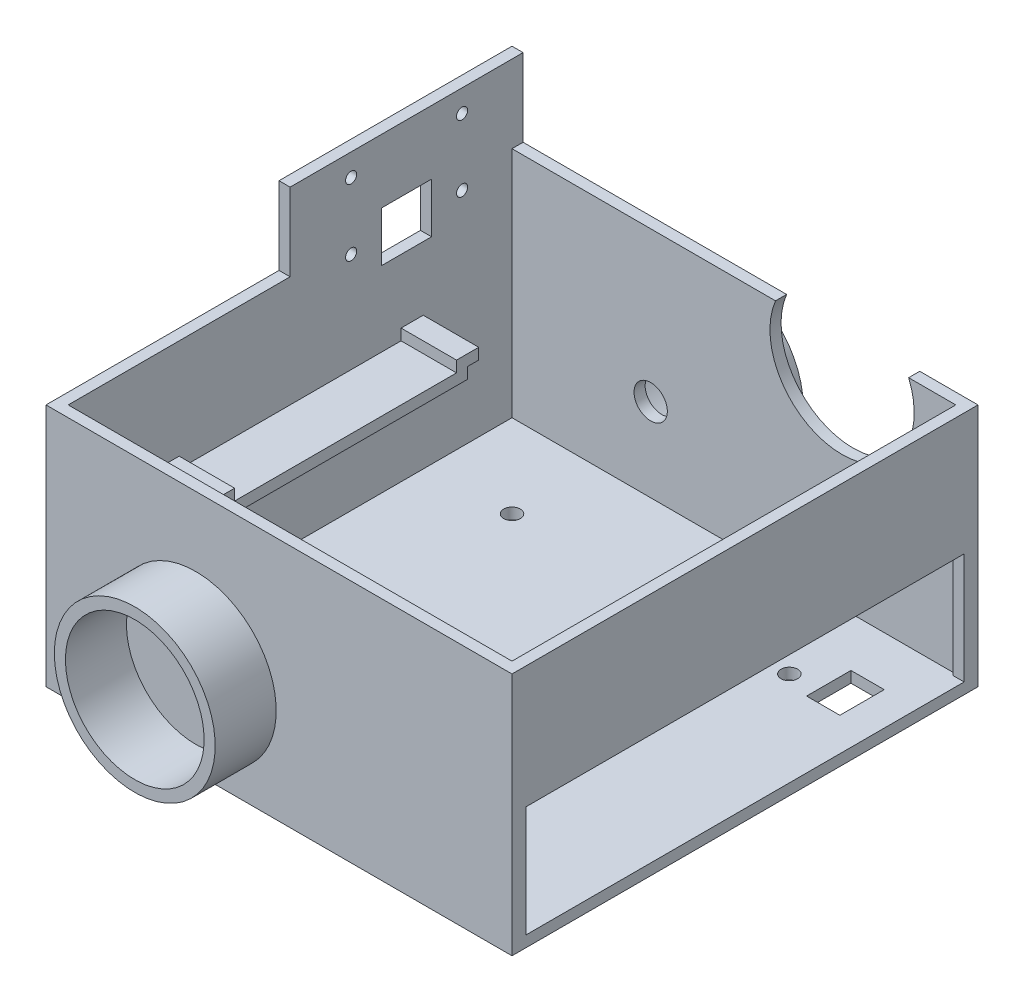
SolidWorks part; units mm, degrees
ref_plane "Front Plane" through (0, 0, 0) normal (0, 0, 1) x (1, 0, 0)
ref_plane "Top Plane" through (0, 0, 0) normal (0, 1, 0) x (1, 0, 0)
ref_plane "Right Plane" through (0, 0, 0) normal (1, 0, 0) x (0, 0, -1)
sketch "Sketch1" plane through (0, 0, 0) normal (0, 1, 0) x (1, 0, 0)
  line L1 (-39, -39) -> (39, -39) construction
  line L2 (-39, -39) -> (-39, 39) construction
  line L3 (-39, 39) -> (39, 39) construction
  line L4 (39, -39) -> (39, 39) construction
  line L5 (-39, -39) -> (39, 39) construction
  line L6 (-39, 39) -> (39, -39) construction
  line L7 (-42, 42) -> (42, 42)
  line L8 (-42, 42) -> (-42, -42)
  line L9 (-42, -42) -> (42, -42)
  line L10 (42, 42) -> (42, -42)
  line L11 (-42, 42) -> (42, -42) construction
  line L12 (-42, -42) -> (42, 42) construction
  point P0 (0, 0)
  point P6 (0, 0)
  dimension "D1" = 78
  dimension "D2" = 84
extrude "Boss-Extrude1" add sketch "Sketch1" along normal mid plane 44
sketch "Sketch2" plane through (0, 22, 0) normal (0, 1, 0) x (1, 0, 0)
  line L0 (-40, 40) -> (-40, 42) construction
  line L1 (40, 40) -> (-40, 40)
  line L2 (40, 40) -> (40, -40)
  line L3 (40, -40) -> (-40, -40)
  line L4 (-40, 40) -> (-40, -40)
  line L5 (40, 40) -> (-40, -40) construction
  line L6 (40, -40) -> (-40, 40) construction
  line L7 (42, 42) -> (-42, 42) construction
  point P0 (0, 0)
  dimension "D1" = 2
extrude "Cut-Extrude1" cut sketch "Sketch2" against normal offset from surface (42 mm away) 2 up to face at (0, -22, 0)
sketch "Sketch3" plane through (0, -20, 0) normal (0, 1, 0) x (1, 0, 0)
  line L1 (39, 39) -> (-39, 39) construction
  line L2 (39, 39) -> (39, -39) construction
  line L3 (39, -39) -> (-39, -39) construction
  line L4 (-39, 39) -> (-39, -39) construction
  line L5 (39, 39) -> (-39, -39) construction
  line L6 (39, -39) -> (-39, 39) construction
  line L7 (30, 31.1) -> (36, 31.1)
  line L8 (30, 31.1) -> (30, 23.1)
  line L9 (30, 23.1) -> (36, 23.1)
  line L10 (36, 31.1) -> (36, 23.1)
  point P0 (0, 0)
  dimension "D1" = 78
  dimension "D2" = 8
  dimension "D3" = 6
  dimension "D4" = 7.9
  dimension "D5" = 3
extrude "Cut-Extrude2" cut sketch "Sketch3" against normal through all
sketch "Sketch4" plane through (-40, 0, 0) normal (1, 0, 0) x (0, 0, -1)
  line L0 (-22, 4) -> (-20, 4)
  line L5 (-20, 4) -> (-20, 2)
  line L6 (-20, 2) -> (20, 2)
  line L7 (20, 2) -> (20, 4)
  line L8 (20, 4) -> (22, 4)
  line L9 (22, 2) -> (22, 0)
  line L10 (22, 0) -> (-22, 0)
  line L11 (-22, 0) -> (-22, 4)
  line L12 (-22, 2) -> (-20, 2) construction
  line L13 (-20, 0) -> (-20, 2) construction
  line L14 (0, 0) -> (0, 2) construction
  line L15 (-40, -20) -> (40, -20) construction
  line L16 (22, 4) -> (24, 4)
  line L17 (24, 4) -> (24, 2)
  line L18 (24, 2) -> (22, 2)
  dimension "D1" = 2
  dimension "D2" = 40
  dimension "D3" = 20
  dimension "D4" = 2
sketch "Sketch5" plane through (42, 0, 0) normal (1, 0, 0) x (0, 0, -1)
  line L0 (-40, -20) -> (40, -20) construction
  line L1 (39.5, 0) -> (-39.5, 0)
  line L2 (39.5, 0) -> (39.5, -20)
  line L3 (39.5, -20) -> (-39.5, -20)
  line L4 (-39.5, 0) -> (-39.5, -20)
  line L5 (39.5, 0) -> (-39.5, -20) construction
  line L6 (39.5, -20) -> (-39.5, 0) construction
  point P0 (0, -10)
  dimension "D1" = 79
  dimension "D2" = 20
extrude "Cut-Extrude3" cut sketch "Sketch5" against normal up to next
extrude "Boss-Extrude2" add sketch "Sketch4" along normal blind 10
mirror "Mirror1" about plane through (0, 0, 0) normal (1, 0, 0) of "Boss-Extrude2"
sketch "Sketch6" plane through (0, 0, -42) normal (0, 0, -1) x (-1, 0, 0)
  line L0 (-30, 4) -> (-40, 4) construction
  line L1 (-42, 22) -> (-42, -22) construction
  circle A0 centre (-19.5, 17) radius 13
  dimension "D1" = 26
  dimension "D2" = 22.5
extrude "Cut-Extrude4" cut sketch "Sketch6" against normal up to next
sketch "Sketch7" plane through (-40, 0, 0) normal (1, 0, 0) x (0, 0, -1)
  line L0 (-40, 9) -> (40, 9) construction
  line L1 (-40, -20) -> (-40, 22) construction
  line L2 (40, -20) -> (40, 22) construction
  line L3 (-20, 4) -> (-22, 4) construction
  line L4 (11, 32) -> (11, 34) construction
  line L5 (9, 9) -> (33, 9) construction
  line L6 (9, 9) -> (9, 34) construction
  line L7 (9, 34) -> (33, 34) construction
  line L8 (33, 9) -> (33, 34) construction
  line L9 (11, 32) -> (31, 32) construction
  line L10 (11, 32) -> (11, 20) construction
  line L11 (11, 20) -> (31, 20) construction
  line L12 (31, 32) -> (31, 20) construction
  line L13 (11, 32) -> (31, 20) construction
  line L14 (11, 20) -> (31, 32) construction
  line L15 (11, 32) -> (9, 32) construction
  line L17 (33, 31) -> (9, 31) construction
  line L18 (33, 31) -> (33, 9) construction
  line L19 (33, 9) -> (9, 9) construction
  line L20 (9, 31) -> (9, 9) construction
  line L21 (33, 31) -> (9, 9) construction
  line L22 (33, 9) -> (9, 31) construction
  line L23 (16.5, 24.5) -> (25.5, 24.5)
  line L24 (16.5, 24.5) -> (16.5, 15.5)
  line L25 (16.5, 15.5) -> (25.5, 15.5)
  line L26 (25.5, 24.5) -> (25.5, 15.5)
  line L27 (16.5, 24.5) -> (25.5, 15.5) construction
  line L28 (16.5, 15.5) -> (25.5, 24.5) construction
  circle A0 centre (31, 32) radius 1
  circle A1 centre (31, 20) radius 1
  circle A2 centre (11, 20) radius 1
  circle A3 centre (11, 32) radius 1
  point P13 (21, 26)
  point P23 (21, 20)
  point P27 (21, 20)
  dimension "D8" = 2
  dimension "D1" = 5
  dimension "D2" = 25
  dimension "D3" = 24
  dimension "D4" = 7
  dimension "D5" = 20
  dimension "D6" = 12
  dimension "D7" = 2
  dimension "D9" = 22
  dimension "D10" = 9
sketch "Sketch8" plane through (0, 22, 0) normal (0, 1, 0) x (1, 0, 0)
  line L0 (-40, -40) -> (-40, 40) construction
  line L1 (-42, 42) -> (-40, 42)
  line L2 (-42, 42) -> (-42, 0)
  line L3 (-42, 0) -> (-40, 0)
  line L4 (-40, 42) -> (-40, 0)
extrude "Boss-Extrude3" add sketch "Sketch8" along normal blind 14
extrude "Cut-Extrude6" cut sketch "Sketch7" against normal up to next
sketch "Sketch9" plane through (0, -20, 0) normal (0, 1, 0) x (1, 0, 0)
  line L1 (-25, 25) -> (25, 25) construction
  line L2 (-25, 25) -> (-25, -25) construction
  line L3 (-25, -25) -> (25, -25) construction
  line L4 (25, 25) -> (25, -25) construction
  line L5 (-25, 25) -> (25, -25) construction
  line L6 (-25, -25) -> (25, 25) construction
  circle A0 centre (-25, 25) radius 1.5
  circle A1 centre (25, 25) radius 1.5
  circle A2 centre (25, -25) radius 1.5
  circle A3 centre (-25, -25) radius 1.5
  point P0 (0, 0)
  dimension "D2" = 3
  dimension "D1" = 50
extrude "Cut-Extrude7" cut sketch "Sketch9" against normal through all
sketch "Sketch10" plane through (-40, 0, 0) normal (1, 0, 0) x (0, 0, -1)
  line L1 (16.5, 15.5) -> (25.5, 15.5)
  line L2 (16.5, 15.5) -> (16.5, 24.5)
  line L3 (16.5, 24.5) -> (25.5, 24.5)
  line L4 (25.5, 15.5) -> (25.5, 24.5)
  line L5 (16.5, 15.5) -> (25.5, 24.5) construction
  line L6 (16.5, 24.5) -> (25.5, 15.5) construction
  point P0 (21, 20)
sketch "Sketch11" plane through (0, -20, 0) normal (0, 1, 0) x (1, 0, 0)
  line L0 (42, 32.1191) -> (32.5, 32.1191) construction
  line L1 (42, -42) -> (42, 42) construction
  line L2 (-42, 32.1191) -> (-18.5, 32.1191) construction
  line L3 (-42, 42) -> (-42, 0) construction
  dimension "D1" = 23.5
  dimension "D2" = 9.5
sketch "Sketch12" plane through (0, 0, -42) normal (0, 0, -1) x (-1, 0, 0)
  line L0 (18.5, -20) -> (18.5, -12) construction
  line L1 (-42, -20) -> (-32.5, -20) construction
  line L2 (-42, -22) -> (42, -22) construction
  line L4 (42, 36) -> (42, -22) construction
  circle A0 centre (18.5, -12) radius 7.5
  dimension "D3" = 15
  dimension "D1" = 10
  dimension "D2" = 23.5
sketch "Sketch14" plane through (0, 0, -40) normal (0, 0, 1) x (1, 0, 0)
  line L0 (-42, 22) -> (-42, -22) construction
  line L2 (-42, -22) -> (42, -22) construction
  circle A0 centre (-15, -5) radius 14.5
  dimension "D1" = 29
  dimension "D2" = 27
  dimension "D3" = 17
extrude "Boss-Extrude4" add sketch "Sketch14" against normal blind 13
sketch "Sketch15" plane through (0, 0, -53) normal (0, 0, -1) x (-1, 0, 0)
  circle A0 centre (15, -5) radius 12.5
  dimension "D1" = 25
extrude "Cut-Extrude8" cut sketch "Sketch15" against normal blind 11
sketch "Sketch16" plane through (0, 0, -42) normal (0, 0, -1) x (-1, 0, 0)
  circle A0 centre (15, -5) radius 3
  circle A1 centre (15, -5) radius 12.5 construction
  dimension "D1" = 6
extrude "Cut-Extrude9" cut sketch "Sketch16" against normal up to next
mirror "Mirror2" about plane through (0, 0, 0) normal (0, 0, 1) of "Cut-Extrude8", "Cut-Extrude9", "Boss-Extrude4"
